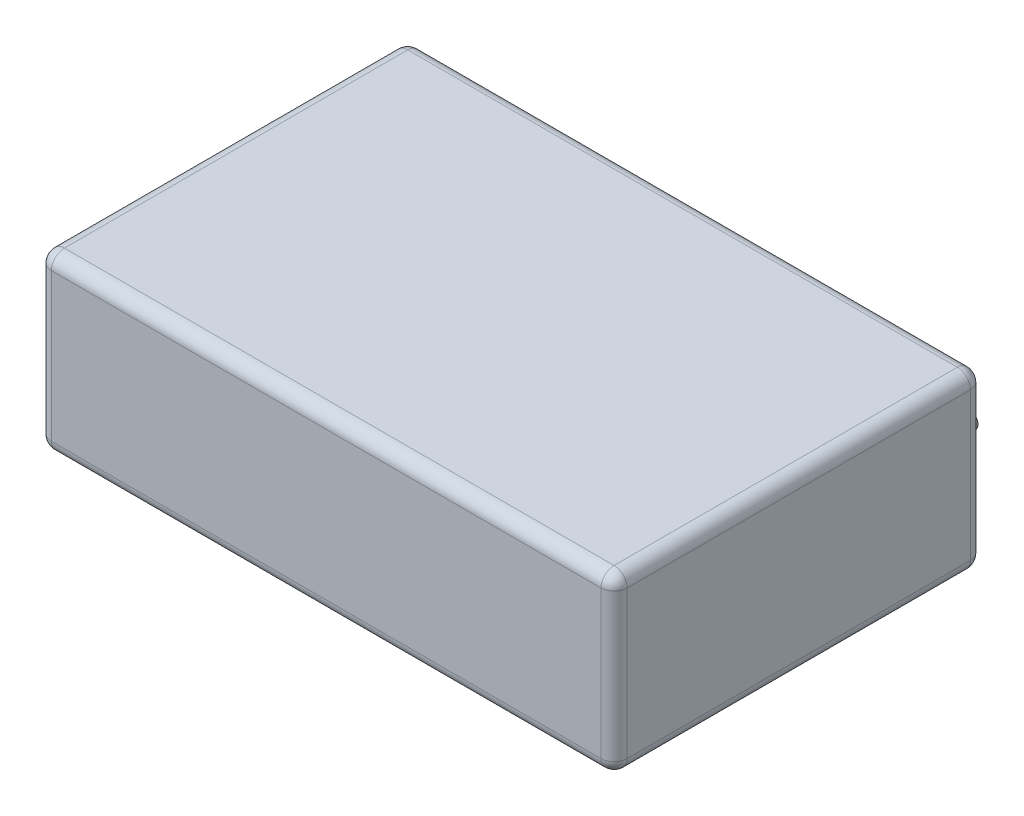
SolidWorks part; units mm, degrees
ref_plane "前视基准面" through (0, 0, 0) normal (0, 0, 1) x (1, 0, 0)
ref_plane "上视基准面" through (0, 0, 0) normal (0, 1, 0) x (1, 0, 0)
ref_plane "右视基准面" through (0, 0, 0) normal (1, 0, 0) x (0, 0, -1)
sketch "草图1" plane through (0, 0, 0) normal (0, 0, 1) x (1, 0, 0)
  line L0 (-1000, 0) -> (49000, 0) construction
  line L1 (0, -1000) -> (0, 49000) construction
  line L2 (13.25, 4) -> (-13.25, 4)
  line L3 (-13.25, 4) -> (-13.25, -4)
  line L4 (13.25, -4) -> (-13.25, -4)
  line L5 (13.25, 4) -> (13.25, -4)
  point P9 (-13.25, 0)
  point P11 (0, -4)
  point P12 (0, 4)
  dimension "D1" = 26.5
  dimension "D2" = 8
extrude "凸台-拉伸1" add sketch "草图1" along normal blind 17
fillet "圆角1" radius 0.6 12 edges at (13.25, 0, 0) (0, 4, 0) (-13.25, 0, 0) (0, -4, 0) (-13.25, 4, 8.5) (-13.25, -4, 8.5) (-13.25, 0, 17) (0, -4, 17) (0, 4, 17) (13.25, 0, 17) (13.25, 4, 8.5) (13.25, -4, 8.5)
sketch "草图2" plane through (0, 0, 0) normal (0, 0, -1) x (-1, 0, 0)
  line L0 (0, -1000) -> (0, 49000) construction
  line L1 (-1000, 0) -> (49000, 0) construction
  circle A0 centre (11, 0) radius 0.4
  circle A1 centre (-11, 0) radius 0.4
  dimension "D1" = 0.8
  dimension "D2" = 22
extrude "凸台-拉伸2" add sketch "草图2" along normal blind 1.6
